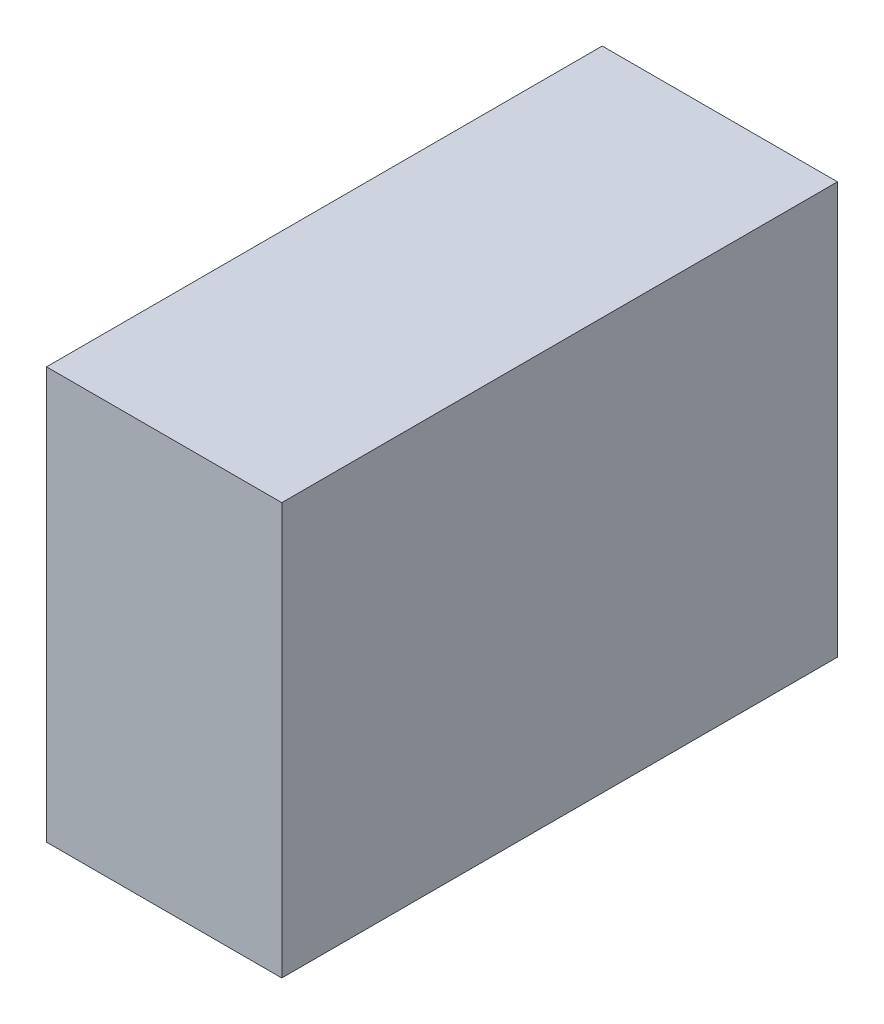
SolidWorks part; units mm, degrees
material "6061 Alloy"
ref_plane "Front Plane" through (0, 0, 0) normal (0, 0, 1) x (1, 0, 0)
ref_plane "Top Plane" through (0, 0, 0) normal (0, 1, 0) x (1, 0, 0)
ref_plane "Right Plane" through (0, 0, 0) normal (1, 0, 0) x (0, 0, -1)
sketch "Sketch1" plane through (0, 0, 0) normal (0, 0, 1) x (1, 0, 0)
  line L1 (-12.7, 22.225) -> (12.7, 22.225)
  line L2 (-12.7, 22.225) -> (-12.7, -22.225)
  line L3 (-12.7, -22.225) -> (12.7, -22.225)
  line L4 (12.7, 22.225) -> (12.7, -22.225)
  line L5 (-12.7, 22.225) -> (12.7, -22.225) construction
  line L6 (-12.7, -22.225) -> (12.7, 22.225) construction
  point P0 (0, 0)
  dimension "D1" = 44.45
  dimension "D2" = 25.4
extrude "Boss-Extrude1" add sketch "Sketch1" along normal blind 60
